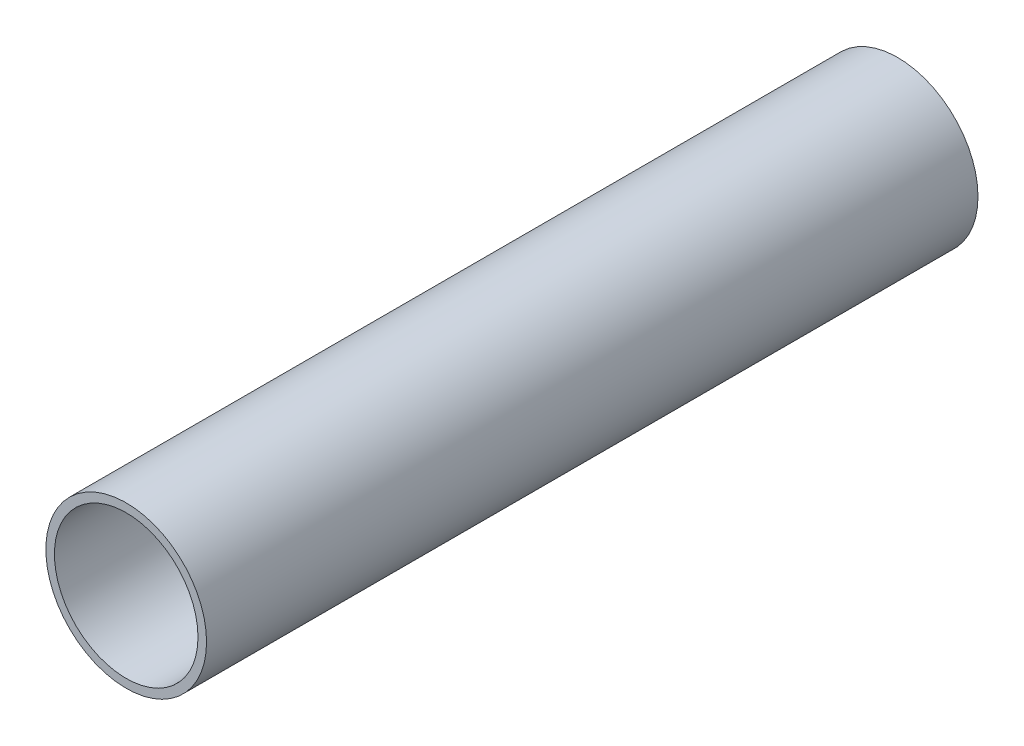
SolidWorks part; units mm, degrees
ref_plane "Front Plane" through (0, 0, 0) normal (0, 0, 1) x (1, 0, 0)
ref_plane "Top Plane" through (0, 0, 0) normal (0, 1, 0) x (1, 0, 0)
ref_plane "Right Plane" through (0, 0, 0) normal (1, 0, 0) x (0, 0, -1)
sketch "Sketch1" plane through (0, 0, 0) normal (0, 0, 1) x (1, 0, 0)
  circle A0 centre (0, 0) radius 1.675
  circle A1 centre (0, 0) radius 1.875
  dimension "D1" = 3.75
  dimension "D2" = 0.2
extrude "Boss-Extrude1" add sketch "Sketch1" along normal blind 18
